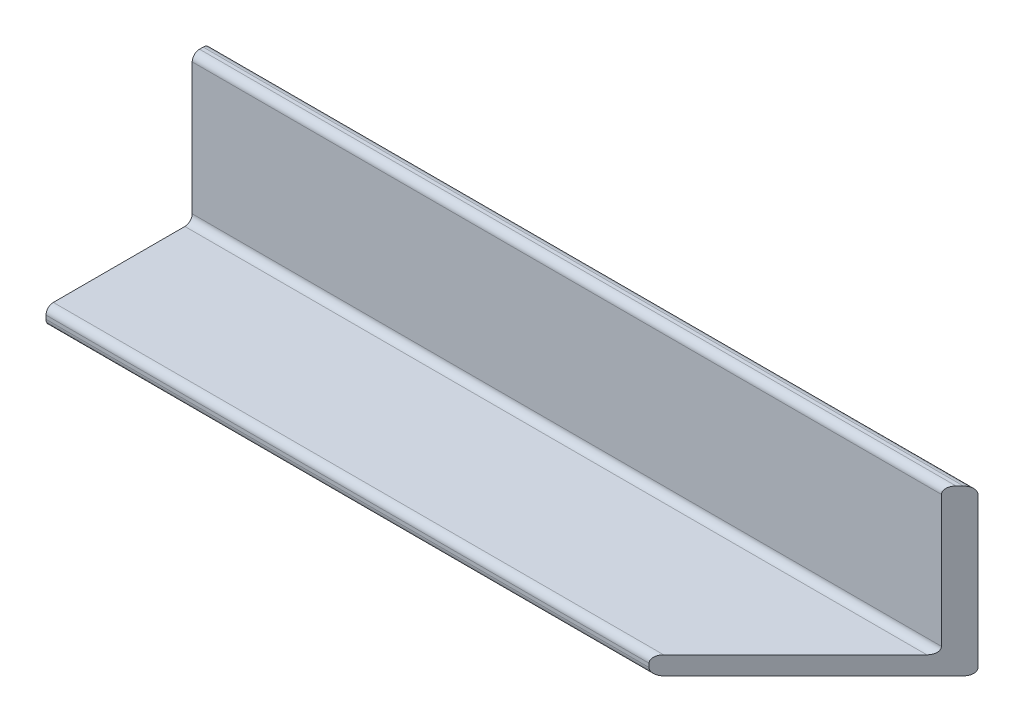
SolidWorks part; units mm, degrees
ref_plane "Front Plane" through (0, 0, 0) normal (0, 0, 1) x (1, 0, 0)
ref_plane "Top Plane" through (0, 0, 0) normal (0, 1, 0) x (1, 0, 0)
ref_plane "Right Plane" through (0, 0, 0) normal (1, 0, 0) x (0, 0, -1)
sketch "Sketch1" plane through (0, 0, 0) normal (0, 1, 0) x (1, 0, 0)
  line L1 (-52.5, 11.25) -> (52.5, 11.25)
  line L2 (-52.5, 11.25) -> (-52.5, -11.25)
  line L3 (-52.5, -11.25) -> (52.5, -11.25)
  line L4 (52.5, 11.25) -> (52.5, -11.25)
  line L5 (-52.5, 11.25) -> (52.5, -11.25) construction
  line L6 (-52.5, -11.25) -> (52.5, 11.25) construction
  point P0 (0, 0)
  dimension "D1" = 105
  dimension "D2" = 22.5
extrude "Boss-Extrude1" add sketch "Sketch1" along normal blind 2.5
sketch "Sketch2" plane through (0, 2.5, 0) normal (0, 1, 0) x (1, 0, 0)
  line L0 (52.5, -11.25) -> (52.5, 11.25) construction
  line L1 (-52.5, 11.25) -> (52.5, 11.25)
  line L2 (-52.5, 11.25) -> (-52.5, 8.75)
  line L3 (-52.5, 8.75) -> (52.5, 8.75)
  line L4 (52.5, 11.25) -> (52.5, 8.75)
  dimension "D1" = 2.5
extrude "Boss-Extrude2" add sketch "Sketch2" along normal blind 20
sketch "Sketch3" plane through (0, 0, 0) normal (0, -1, 0) x (-1, 0, 0)
  line L0 (-52.5, -11.25) -> (-52.5, 11.25)
  line L1 (-52.5, 11.25) -> (-30, -11.25)
  line L2 (52.5, -11.25) -> (-52.5, -11.25) construction
  line L3 (-30, -11.25) -> (-52.5, -11.25)
  dimension "D1" = 45
extrude "Cut-Extrude1" cut sketch "Sketch3" against normal through all
fillet "Fillet1" radius 1 6 edges at (-11.25, 2.5, 11.25) (-11.25, 0, 11.25) (-1.25, 22.5, -8.75) (0, 22.5, -11.25) (0, 0, -11.25) (-1.25, 2.5, -8.75)
